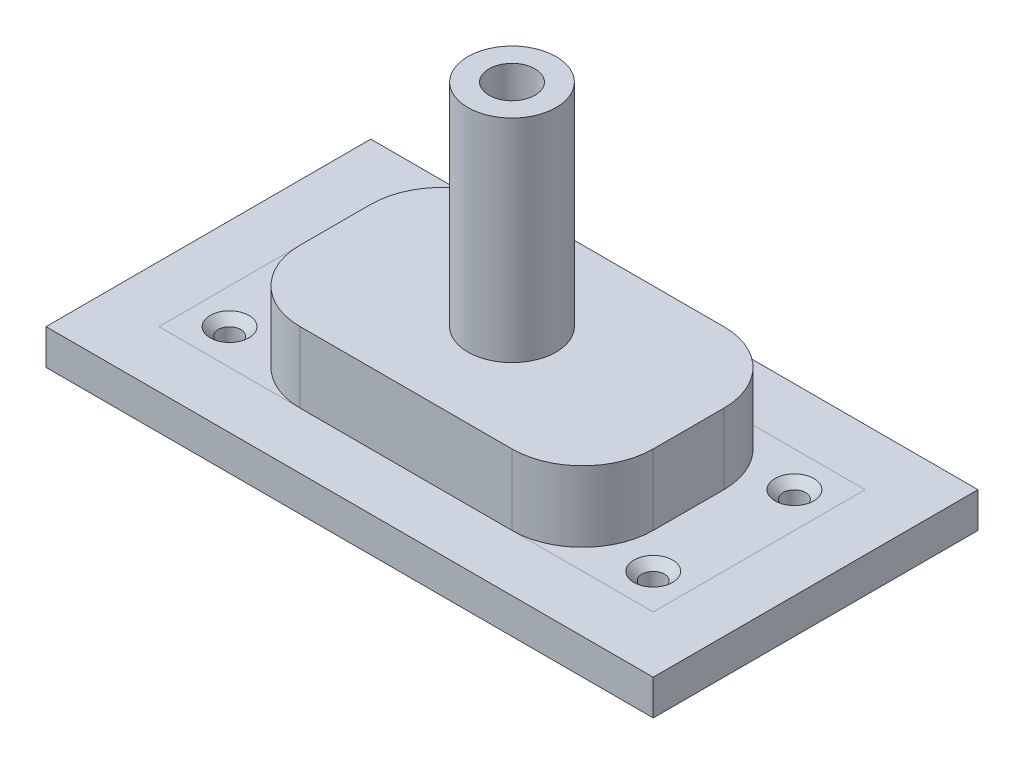
SolidWorks part; units mm, degrees
ref_plane "Front Plane" through (0, 0, 0) normal (0, 0, 1) x (1, 0, 0)
ref_plane "Top Plane" through (0, 0, 0) normal (0, 1, 0) x (1, 0, 0)
ref_plane "Right Plane" through (0, 0, 0) normal (1, 0, 0) x (0, 0, -1)
sketch "Sketch1" plane through (0, 0, 0) normal (0, 1, 0) x (1, 0, 0)
  line L1 (35, -15) -> (-35, -15)
  line L2 (35, -15) -> (35, 15)
  line L3 (35, 15) -> (-35, 15)
  line L4 (-35, -15) -> (-35, 15)
  line L5 (35, -15) -> (-35, 15) construction
  line L6 (35, 15) -> (-35, -15) construction
  point P0 (0, 0)
  dimension "D1" = 70
  dimension "D2" = 30
extrude "Boss-Extrude1" add sketch "Sketch1" along normal blind 15
sketch "Sketch2" plane through (0, 0, 0) normal (0, -1, 0) x (-1, 0, 0)
  line L0 (35, 15) -> (35, -15) construction
  line L1 (35, -15) -> (-35, -15) construction
  line L2 (0, -15) -> (0, 15) construction
  line L3 (-35, 15) -> (35, 15) construction
  line L4 (-27, 7) -> (27, 7)
  line L5 (-35, -15) -> (-35, 15) construction
  line L6 (-35, 0) -> (0, 0) construction
  line L7 (-27, 7) -> (-27, -7)
  line L8 (-27, -7) -> (27, -7)
  line L9 (27, 7) -> (27, -7)
  line L10 (-27, 7) -> (27, -7) construction
  line L11 (-27, -7) -> (27, 7) construction
  point P15 (35, 0)
  dimension "D1" = 8
  dimension "D2" = 8
extrude "Cut-Extrude1" cut sketch "Sketch2" against normal blind 40 draft 35
sketch "Sketch3" plane through (0, 15, 0) normal (0, 1, 0) x (1, 0, 0)
  circle A0 centre (0, 0) radius 6.25
  dimension "D1" = 12.5
extrude "Boss-Extrude2" add sketch "Sketch3" along normal blind 30
sketch "Sketch4" plane through (0, 45, 0) normal (0, 1, 0) x (1, 0, 0)
  circle A0 centre (0, 0) radius 3.25
  circle A1 centre (0, 0) radius 6.25 construction
  dimension "D1" = 3
extrude "Cut-Extrude2" cut sketch "Sketch4" against normal through all
sketch "Sketch8" plane through (0, 0, 0) normal (0, -1, 0) x (1, 0, 0)
  line L1 (-35, 15) -> (35, 15)
  line L2 (-35, 15) -> (-35, -15)
  line L3 (-35, -15) -> (35, -15)
  line L4 (35, 15) -> (35, -15)
  line L5 (43, -23) -> (-43, -23)
  line L6 (43, -23) -> (43, 23)
  line L7 (43, 23) -> (-43, 23)
  line L8 (-43, -23) -> (-43, 23)
  line L9 (43, -23) -> (-43, 23) construction
  line L10 (43, 23) -> (-43, -23) construction
  point P4 (0, 0)
  dimension "D1" = 8
  dimension "D2" = 8
extrude "Boss-Extrude4" add sketch "Sketch8" against normal blind 5 separate body
sketch "Sketch9" plane through (0, 0, 0) normal (0, -1, 0) x (1, 0, 0)
  line L0 (27, 7) -> (-27, 7) construction
  line L1 (-27, -7) -> (-27, 7) construction
  line L2 (0, 0) -> (0, 15) construction
  line L4 (-35, -15) -> (-35, 15) construction
  line L5 (-35, 0) -> (0, 0) construction
  circle A0 centre (-30, 10) radius 1.6
  circle A1 centre (30, 10) radius 1.6
  circle A2 centre (30, -10) radius 1.6
  circle A3 centre (-30, -10) radius 1.6
  dimension "D1" = 3.2
  dimension "D2" = 3
  dimension "D3" = 3
extrude "Cut-Extrude4" cut sketch "Sketch9" against normal up to surface (15 mm away) up to face at (0, 15, 0)
sketch "Sketch10" plane through (0, 15, 0) normal (0, 1, 0) x (1, 0, 0)
  line L0 (0, 0) -> (0, 31.129) construction
  line L1 (-35, 15) -> (-25, 15)
  line L2 (-35, 15) -> (-35, -15)
  line L3 (-35, -15) -> (-25, -15)
  line L4 (-25, 15) -> (-25, -15)
  line L5 (-35, -15) -> (35, -15) construction
  line L6 (-35, 15) -> (-35, -15) construction
  line L7 (-35, 0) -> (0, 0) construction
  line L8 (25, 15) -> (25, -15)
  line L9 (35, -15) -> (25, -15)
  line L10 (35, 15) -> (35, -15)
  line L11 (35, 15) -> (25, 15)
  circle A1 centre (-30, 10) radius 1.6 construction
  dimension "D1" = 5
extrude "Screw Block Cut Outs" cut sketch "Sketch10" against normal up to surface (10 mm away) up to face at (0, 5, 0)
fillet "Fillet1" radius 10 1 edges at (-25, 10, 15)
fillet "Fillet2" radius 10 1 edges at (-25, 10, -15)
fillet "Fillet3" radius 10 1 edges at (25, 10, 15)
fillet "Fillet4" radius 10 1 edges at (25, 10, -15)
sketch "Sketch11" plane through (0, 0, 0) normal (0, -1, 0) x (1, 0, 0)
  line L0 (-39, -19) -> (-39, 19)
  line L1 (-39, 19) -> (39, 19)
  line L2 (39, 19) -> (39, -19)
  line L3 (39, -19) -> (-39, -19)
  line L4 (-37, -17) -> (-37, 17)
  line L5 (-37, 17) -> (37, 17)
  line L6 (37, 17) -> (37, -17)
  line L7 (37, -17) -> (-37, -17)
  line L8 (-35, 15) -> (-35, -15) construction
  line L9 (35, 15) -> (-35, 15) construction
  line L11 (-35, -15) -> (35, -15) construction
  line L13 (35, -15) -> (35, 15) construction
  dimension "D1" = 2
  dimension "D2" = 2
  dimension "D3" = 2
  dimension "D4" = 2
  dimension "D5" = 2
  dimension "D6" = 2
  dimension "D7" = 2
  dimension "D8" = 2
extrude "Sealant Cut" cut sketch "Sketch11" against normal blind 2 draft 30
sketch "Sketch13" plane through (0, 5, 0) normal (0, 1, 0) x (1, 0, 0)
  line L0 (0, 0) -> (0, -23) construction
  line L1 (43, -23) -> (-43, -23) construction
  line L3 (43, 23) -> (43, -23) construction
  line L4 (43, 0) -> (0, 0) construction
  circle A0 centre (30, -10) radius 2.75
  circle A1 centre (-30, -10) radius 2.75
  circle A2 centre (-30, 10) radius 2.75
  circle A3 centre (30, 10) radius 2.75
  dimension "D1" = 5.5
extrude "Screw HEads" cut sketch "Sketch13" against normal blind 2 draft 45
